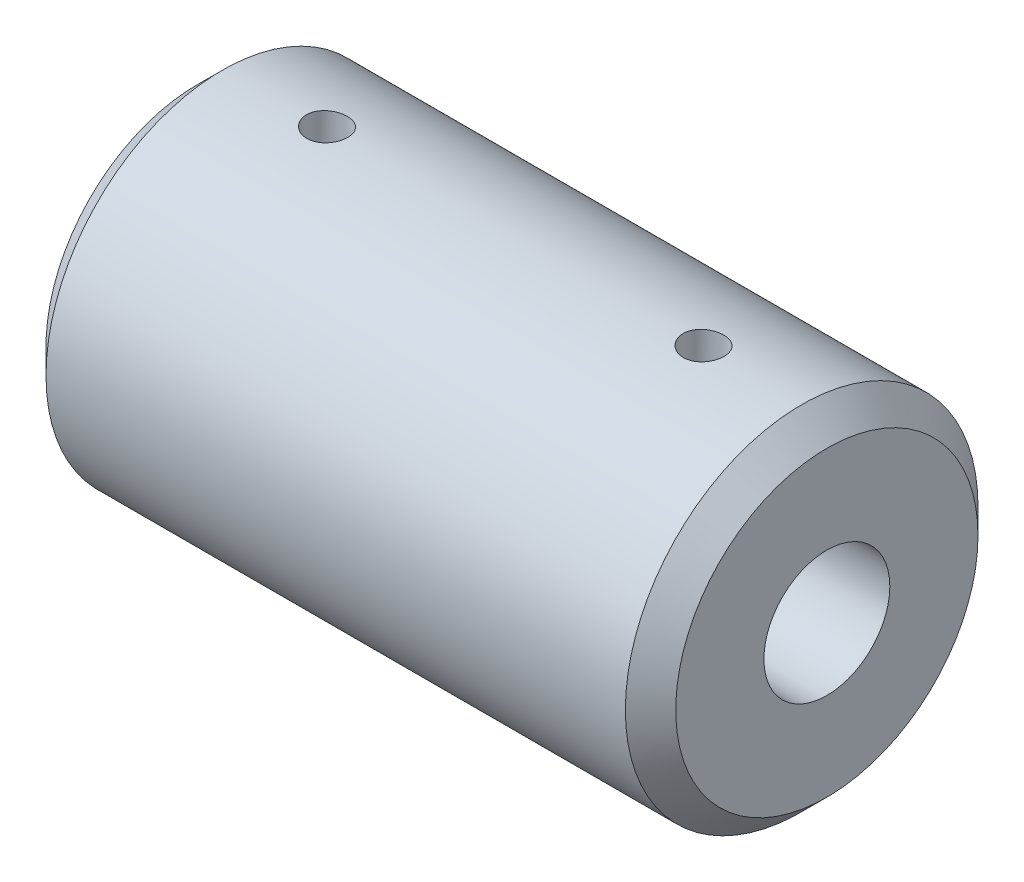
SolidWorks part; units mm, degrees
ref_plane "Alzado" through (0, 0, 0) normal (0, 0, 1) x (1, 0, 0)
ref_plane "Planta" through (0, 0, 0) normal (0, 1, 0) x (1, 0, 0)
ref_plane "Vista lateral" through (0, 0, 0) normal (1, 0, 0) x (0, 0, -1)
sketch "Croquis1" plane through (0, 0, 0) normal (1, 0, 0) x (0, 0, -1)
  line L0 (0, 7) -> (0, -7) construction
  circle A0 centre (0, 0) radius 7
  dimension "D1" = 14
extrude "Saliente-Extruir1" add sketch "Croquis1" along normal blind 25
sketch "Croquis2" plane through (25, 0, 0) normal (1, 0, 0) x (0, 0, -1)
  circle A0 centre (0, 0) radius 2.5
  dimension "D1" = 5
extrude "Cortar-Extruir1" cut sketch "Croquis2" against normal blind 12.5
sketch "Croquis3" plane through (0, 0, 0) normal (-1, 0, 0) x (0, 0, 1)
  circle A0 centre (0, 0) radius 4
  dimension "D1" = 8
extrude "Cortar-Extruir2" cut sketch "Croquis3" against normal blind 12.5
chamfer "Chaflán1" distance 1 angle 45 1 edges at (25, 0, -7)
chamfer "Chaflán2" distance 1 angle 45 1 edges at (0, 0, -7)
hole_wizard "Taladro de margen para M1.41" positions "Croquis3D3" profile "Croquis6" hole size "M1.4" standard "ISO"
sketch3d "Croquis3D3"
  point P0 (5, 6.9982, -0.158)
  dimension "D1" = 5
sketch "Croquis6" plane through (5, 6.9982, -0.158) normal (1, 0, 0) x (0, 0.0226, 0.9997)
  line L0 (0, 0) -> (0, 3)
  line L1 (0, 3) -> (0.8, 3)
  line L2 (0.8, 3) -> (0.8, 0)
  line L5 (0.8, 0) -> (0, 0)
  line L11 (0, -6.35) -> (0, 107.95) construction
  dimension "Diámetro de taladro hasta el siguiente" = 1.6
  dimension "Profundidad de taladro hasta el siguiente" = 3
hole_wizard "Taladro de margen para M1.42" positions "Croquis3D4" profile "Croquis7" hole size "M1.4" standard "ISO"
sketch3d "Croquis3D4"
  point P0 (20, 6.9992, -0.1054)
  dimension "D1" = 5
sketch "Croquis7" plane through (20, 6.9992, -0.1054) normal (1, 0, 0) x (0, 0.0151, 0.9999)
  line L0 (0, 0) -> (0, 4.5)
  line L1 (0, 4.5) -> (0.8, 4.5)
  line L2 (0.8, 4.5) -> (0.8, 0)
  line L5 (0.8, 0) -> (0, 0)
  line L11 (0, -6.35) -> (0, 107.95) construction
  dimension "Diámetro de taladro hasta el siguiente" = 1.6
  dimension "Profundidad de taladro hasta el siguiente" = 4.5
